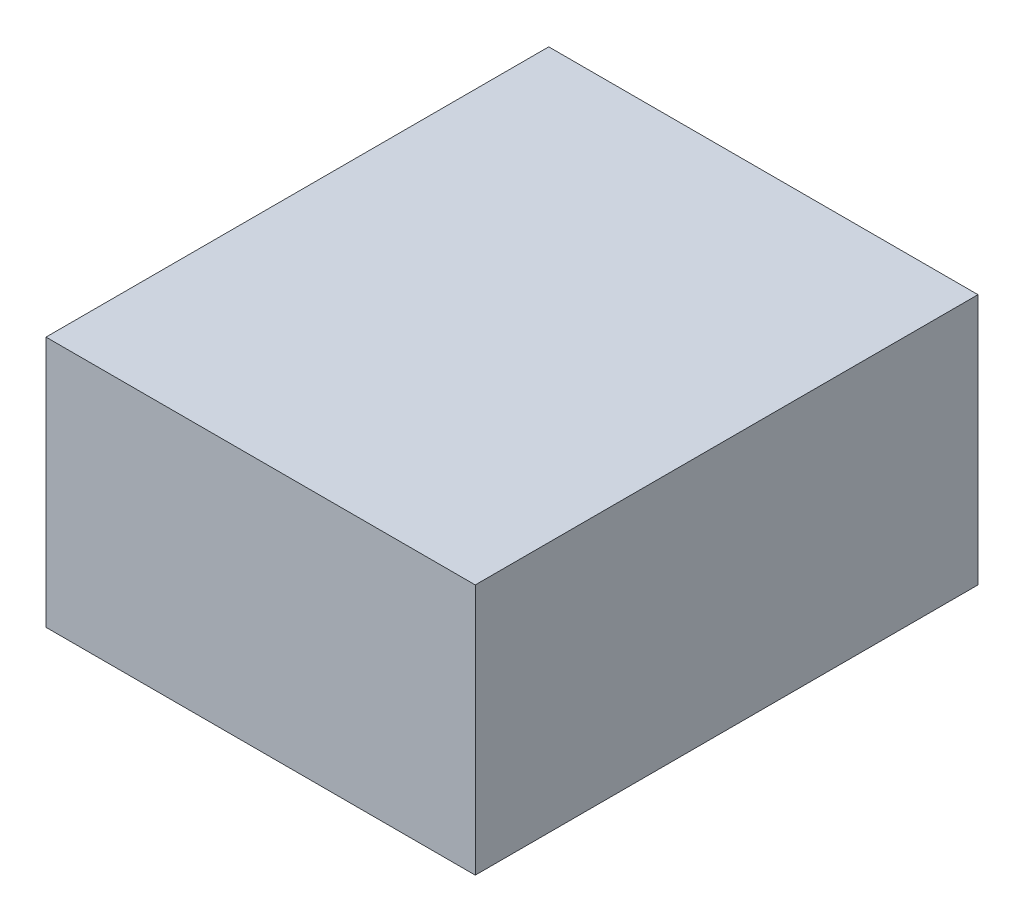
SolidWorks part; units mm, degrees
ref_plane "Front Plane" through (0, 0, 0) normal (0, 0, 1) x (1, 0, 0)
ref_plane "Top Plane" through (0, 0, 0) normal (0, 1, 0) x (1, 0, 0)
ref_plane "Right Plane" through (0, 0, 0) normal (1, 0, 0) x (0, 0, -1)
sketch "Sketch1" plane through (0, 0, 0) normal (0, 1, 0) x (1, 0, 0)
  line L1 (-72.61, 93.899) -> (38.39, 93.899)
  line L2 (-72.61, 93.899) -> (-72.61, -36.101)
  line L3 (-72.61, -36.101) -> (38.39, -36.101)
  line L4 (38.39, 93.899) -> (38.39, -36.101)
extrude "Boss-Extrude1" add sketch "Sketch1" along normal blind 65
